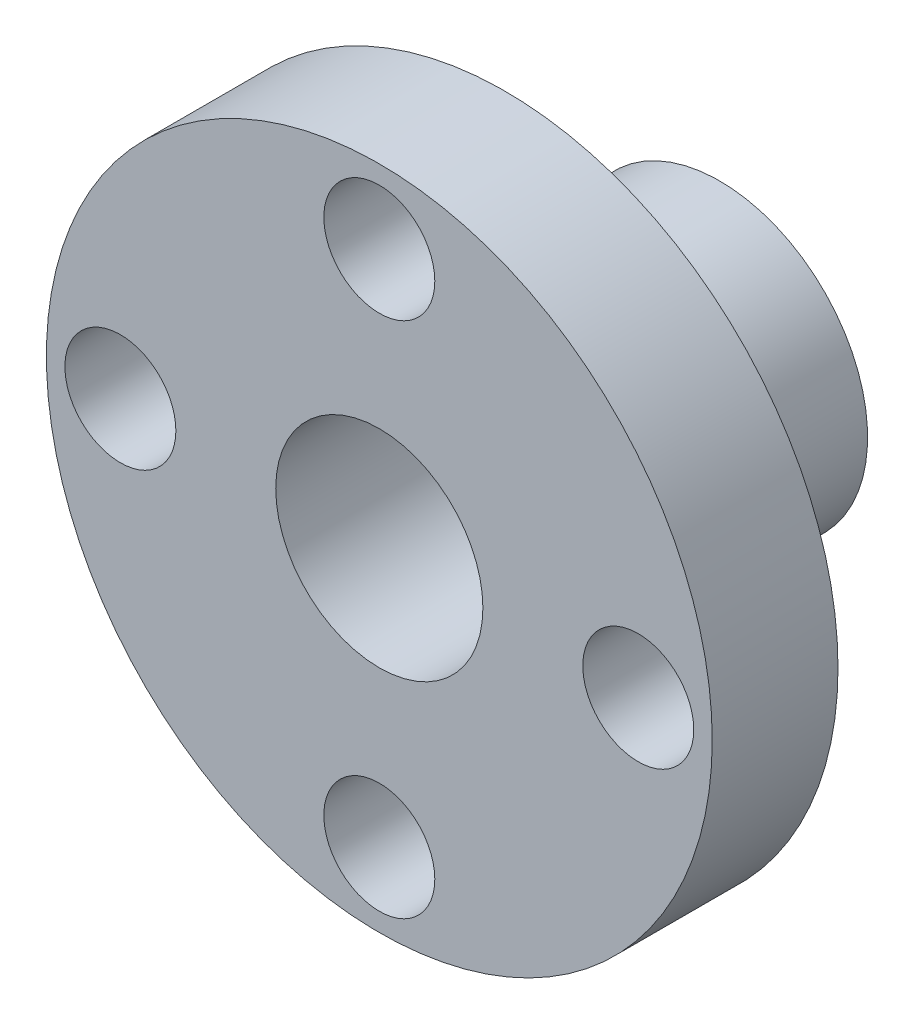
SolidWorks part; units mm, degrees
ref_plane "Front Plane" through (0, 0, 0) normal (0, 0, 1) x (1, 0, 0)
ref_plane "Top Plane" through (0, 0, 0) normal (0, 1, 0) x (1, 0, 0)
ref_plane "Right Plane" through (0, 0, 0) normal (1, 0, 0) x (0, 0, -1)
sketch "Sketch2" plane through (0, 0, 0) normal (0, 0, 1) x (1, 0, 0)
  circle A0 centre (0, 0) radius 225
  circle A1 centre (0, 0) radius 100
extrude "Boss-Extrude1" add sketch "Sketch2" along normal blind 85
sketch "Sketch3" plane through (0, 0, 0) normal (0, 0, -1) x (-1, 0, 0)
  circle A0 centre (0, 0) radius 100
extrude "Boss-Extrude2" add sketch "Sketch3" along normal blind 145 and the other way blind 85
sketch "Sketch4" plane through (0, 0, -145) normal (0, 0, -1) x (-1, 0, 0)
  circle A0 centre (0, 0) radius 70
extrude "Cut-Extrude1" cut sketch "Sketch4" against normal blind 315
sketch "Sketch5" plane through (0, 0, 85) normal (0, 0, 1) x (1, 0, 0)
  circle A2 centre (175, 0) radius 37.5
  circle A3 centre (0, 175) radius 37.5
  circle A4 centre (-175, 0) radius 37.5
  circle A5 centre (0, -175) radius 37.5
extrude "Cut-Extrude2" cut sketch "Sketch5" against normal blind 85
